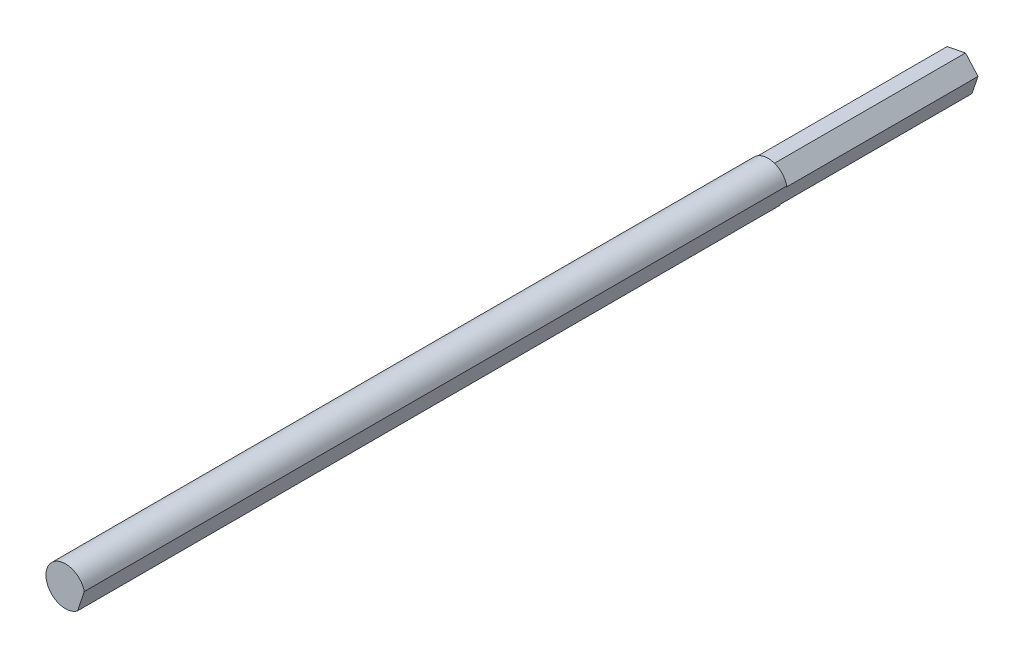
SolidWorks part; units mm, degrees
ref_plane "前视基准面" through (0, 0, 0) normal (0, 0, 1) x (1, 0, 0)
ref_plane "上视基准面" through (0, 0, 0) normal (0, 1, 0) x (1, 0, 0)
ref_plane "右视基准面" through (0, 0, 0) normal (1, 0, 0) x (0, 0, -1)
other "Configuration Table"
sketch "草图1" plane through (0, 0, 0) normal (0, 0, 1) x (1, 0, 0)
  circle A0 centre (0, 0) radius 3.05
  dimension "D1" = 6.1
extrude "凸台-拉伸1" add sketch "草图1" against normal blind 110
sketch "草图2" plane through (0, 0, -110) normal (0, 0, -1) x (-1, 0, 0)
  line L1 (1.9534, 2.2106) -> (-0.9378, 2.797)
  line L2 (-0.9378, 2.797) -> (-2.8911, 0.5863)
  line L3 (-2.8911, 0.5863) -> (-1.9534, -2.2106)
  line L4 (-1.9534, -2.2106) -> (0.9378, -2.797)
  line L5 (0.9378, -2.797) -> (2.8911, -0.5863)
  line L6 (2.8911, -0.5863) -> (1.9534, 2.2106)
  circle A0 centre (0, 0) radius 2.5548 construction
  point P1 (0, 0)
  point P12 (0, 0)
  dimension "D1" = 5.9
extrude "凸台-拉伸2" add sketch "草图2" along normal blind 30
sketch "草图3" plane through (2.4222, -0.8121, 0) normal (0.9481, -0.3179, 0) x (0, 0, -1)
  line L1 (-5.583, 10.4847) -> (142.8785, 10.4847)
  line L2 (-5.583, 10.4847) -> (-5.583, -11.5069)
  line L3 (-5.583, -11.5069) -> (142.8785, -11.5069)
  line L4 (142.8785, 10.4847) -> (142.8785, -11.5069)
extrude "切除-拉伸1" cut sketch "草图3" along normal through all
